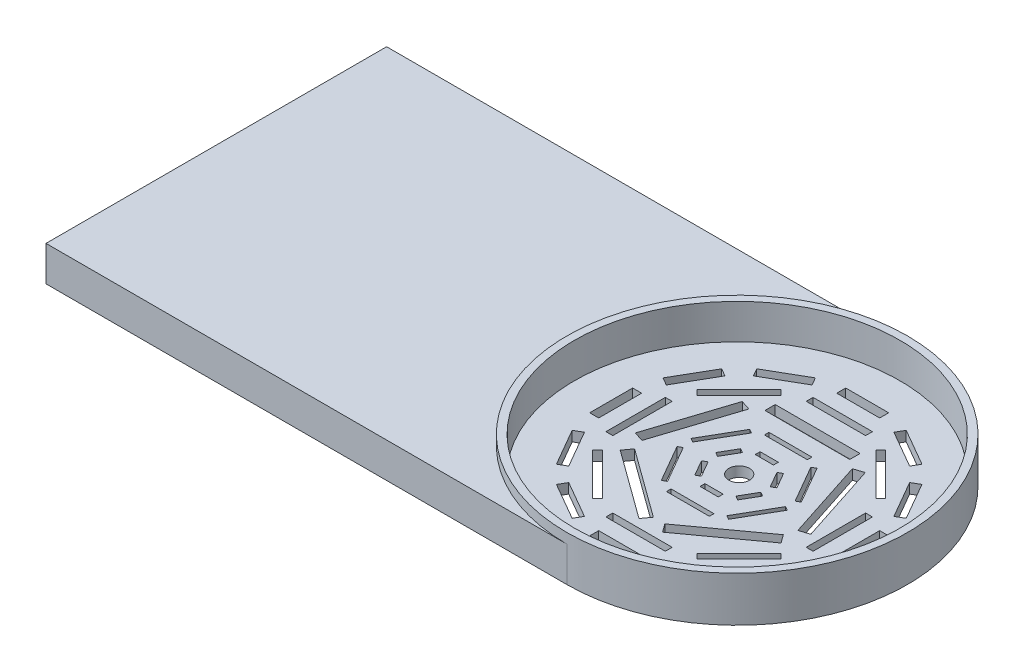
SolidWorks part; units mm, degrees
ref_plane "前视基准面" through (0, 0, 0) normal (0, 0, 1) x (1, 0, 0)
ref_plane "上视基准面" through (0, 0, 0) normal (0, 1, 0) x (1, 0, 0)
ref_plane "右视基准面" through (0, 0, 0) normal (1, 0, 0) x (0, 0, -1)
sketch "草图1" plane through (0, 0, 0) normal (0, 1, 0) x (1, 0, 0)
sketch "草图2" plane through (0, 0, 0) normal (0, 1, 0) x (1, 0, 0)
  circle A1 centre (0, 0) radius 32.5
extrude "凸台-拉伸2" add sketch "草图2" along normal blind 2
sketch "草图3" plane through (0, 2, 0) normal (0, 1, 0) x (1, 0, 0)
  line L0 (4.4198, 4.8381) -> (3.5774, 4.3517)
  line L1 (-1.6852, 6.2644) -> (1.9493, 6.2644)
  line L2 (-1.6852, 6.2644) -> (-1.6852, 5.2916)
  line L3 (-1.6852, 5.2916) -> (1.9493, 5.2916)
  line L4 (1.9493, 6.2644) -> (1.9493, 5.2916)
  line L5 (-1.6852, 6.2644) -> (1.9493, 5.2916) construction
  line L6 (-1.6852, 5.2916) -> (1.9493, 6.2644) construction
  line L7 (4.4198, 4.8381) -> (6.237, 1.6905)
  line L8 (6.237, 1.6905) -> (5.3946, 1.2041)
  line L9 (3.5774, 4.3517) -> (5.3946, 1.2041)
  line L10 (6.237, -1.1622) -> (5.3946, -0.6758)
  line L11 (6.237, -1.1622) -> (4.4198, -4.3097)
  line L12 (4.4198, -4.3097) -> (3.5774, -3.8234)
  line L13 (5.3946, -0.6758) -> (3.5774, -3.8234)
  line L14 (1.9493, -5.736) -> (1.9493, -4.7633)
  line L15 (1.9493, -5.736) -> (-1.6852, -5.736)
  line L16 (-1.6852, -5.736) -> (-1.6852, -4.7633)
  line L17 (1.9493, -4.7633) -> (-1.6852, -4.7633)
  line L18 (-4.1556, -4.3097) -> (-3.3132, -3.8234)
  line L19 (-4.1556, -4.3097) -> (-5.9729, -1.1622)
  line L20 (-5.9729, -1.1622) -> (-5.1305, -0.6758)
  line L21 (-3.3132, -3.8234) -> (-5.1305, -0.6758)
  line L22 (-5.9729, 1.6905) -> (-5.1305, 1.2041)
  line L23 (-5.9729, 1.6905) -> (-4.1556, 4.8381)
  line L24 (-4.1556, 4.8381) -> (-3.3132, 4.3517)
  line L25 (-5.1305, 1.2041) -> (-3.3132, 4.3517)
  line L26 (6.8534, 9.0957) -> (10.35, 1.2124) construction
  line L27 (-4.1556, 10.5008) -> (4.4198, 10.5008)
  line L28 (-4.1556, 10.5008) -> (-4.1556, 9.5872)
  line L29 (-4.1556, 9.5872) -> (4.4198, 9.5872)
  line L30 (4.4198, 10.5008) -> (4.4198, 9.5872)
  line L31 (-4.1556, 10.5008) -> (4.4198, 9.5872) construction
  line L32 (-4.1556, 9.5872) -> (4.4198, 10.5008) construction
  line L33 (6.0623, 8.639) -> (11.1411, 1.6692) construction
  line L34 (6.8534, 9.0957) -> (6.0623, 8.639)
  line L35 (6.8534, 9.0957) -> (11.1411, 1.6692)
  line L36 (11.1411, 1.6692) -> (10.35, 1.2124)
  line L37 (6.0623, 8.639) -> (10.35, 1.2124)
  line L38 (11.1411, -1.1409) -> (6.0623, -8.1106) construction
  line L39 (10.35, -0.6841) -> (6.8534, -8.5674) construction
  line L40 (11.1411, -1.1409) -> (10.35, -0.6841)
  line L41 (11.1411, -1.1409) -> (6.8534, -8.5674)
  line L42 (6.8534, -8.5674) -> (6.0623, -8.1106)
  line L43 (10.35, -0.6841) -> (6.0623, -8.1106)
  line L44 (4.4198, -9.9725) -> (-4.1556, -9.0589) construction
  line L45 (4.4198, -9.0589) -> (-4.1556, -9.9725) construction
  line L46 (4.4198, -9.9725) -> (4.4198, -9.0589)
  line L47 (4.4198, -9.9725) -> (-4.1556, -9.9725)
  line L48 (-4.1556, -9.9725) -> (-4.1556, -9.0589)
  line L49 (4.4198, -9.0589) -> (-4.1556, -9.0589)
  line L50 (-6.5893, -8.5674) -> (-10.0858, -0.6841) construction
  line L51 (-5.7981, -8.1106) -> (-10.877, -1.1409) construction
  line L52 (-6.5893, -8.5674) -> (-5.7981, -8.1106)
  line L53 (-6.5893, -8.5674) -> (-10.877, -1.1409)
  line L54 (-10.877, -1.1409) -> (-10.0858, -0.6841)
  line L55 (-5.7981, -8.1106) -> (-10.0858, -0.6841)
  line L56 (-10.877, 1.6692) -> (-5.7981, 8.639) construction
  line L57 (-10.0858, 1.2124) -> (-6.5893, 9.0957) construction
  line L58 (-10.877, 1.6692) -> (-10.0858, 1.2124)
  line L59 (-10.877, 1.6692) -> (-6.5893, 9.0957)
  line L60 (-6.5893, 9.0957) -> (-5.7981, 8.639)
  line L61 (-10.0858, 1.2124) -> (-5.7981, 8.639)
  line L62 (12.4151, 13.1606) -> (15.6938, -3.585) construction
  line L63 (-8.3375, 15.9312) -> (8.6017, 15.9312)
  line L64 (-8.3375, 15.9312) -> (-8.3375, 13.8748)
  line L65 (-8.3375, 13.8748) -> (8.6017, 13.8748)
  line L66 (8.6017, 15.9312) -> (8.6017, 13.8748)
  line L67 (-8.3375, 15.9312) -> (8.6017, 13.8748) construction
  line L68 (-8.3375, 13.8748) -> (8.6017, 15.9312) construction
  line L69 (10.4593, 12.5252) -> (17.6496, -2.9495) construction
  line L70 (12.4151, 13.1606) -> (10.4593, 12.5252)
  line L71 (12.4151, 13.1606) -> (17.6496, -2.9495)
  line L72 (17.6496, -2.9495) -> (15.6938, -3.585)
  line L73 (10.4593, 12.5252) -> (15.6938, -3.585)
  line L74 (16.193, -7.4324) -> (1.2802, -15.7254) construction
  line L75 (14.9843, -5.7688) -> (2.4889, -17.389) construction
  line L76 (16.193, -7.4324) -> (14.9843, -5.7688)
  line L77 (16.193, -7.4324) -> (2.4889, -17.389)
  line L78 (2.4889, -17.389) -> (1.2802, -15.7254)
  line L79 (14.9843, -5.7688) -> (1.2802, -15.7254)
  line L80 (-2.2247, -17.389) -> (-14.7201, -5.7688) construction
  line L81 (-1.016, -15.7254) -> (-15.9288, -7.4324) construction
  line L82 (-2.2247, -17.389) -> (-1.016, -15.7254)
  line L83 (-2.2247, -17.389) -> (-15.9288, -7.4324)
  line L84 (-15.9288, -7.4324) -> (-14.7201, -5.7688)
  line L85 (-1.016, -15.7254) -> (-14.7201, -5.7688)
  line L86 (-17.3854, -2.9495) -> (-10.1952, 12.5252) construction
  line L87 (-15.4297, -3.585) -> (-12.1509, 13.1606) construction
  line L88 (-17.3854, -2.9495) -> (-15.4297, -3.585)
  line L89 (-17.3854, -2.9495) -> (-12.1509, 13.1606)
  line L90 (-12.1509, 13.1606) -> (-10.1952, 12.5252)
  line L91 (-15.4297, -3.585) -> (-10.1952, 12.5252)
  line L92 (9.2005, 24.5465) -> (15.7273, 18.7005) construction
  line L93 (-4.1556, 25.8275) -> (4.4198, 25.8275)
  line L94 (-4.1556, 25.8275) -> (-4.1556, 24.0282)
  line L95 (-4.1556, 24.0282) -> (4.4198, 24.0282)
  line L96 (4.4198, 25.8275) -> (4.4198, 24.0282)
  line L97 (-4.1556, 25.8275) -> (4.4198, 24.0282) construction
  line L98 (-4.1556, 24.0282) -> (4.4198, 25.8275) construction
  line L99 (8.3008, 22.9882) -> (16.627, 20.2588) construction
  line L100 (9.2005, 24.5465) -> (8.3008, 22.9882)
  line L101 (9.2005, 24.5465) -> (16.627, 20.2588)
  line L102 (16.627, 20.2588) -> (15.7273, 18.7005)
  line L103 (8.3008, 22.9882) -> (15.7273, 18.7005)
  line L104 (20.1267, 16.7591) -> (22.8562, 8.4329) construction
  line L105 (18.5685, 15.8594) -> (24.4144, 9.3326) construction
  line L106 (20.1267, 16.7591) -> (18.5685, 15.8594)
  line L107 (20.1267, 16.7591) -> (24.4144, 9.3326)
  line L108 (24.4144, 9.3326) -> (22.8562, 8.4329)
  line L109 (18.5685, 15.8594) -> (22.8562, 8.4329)
  line L110 (25.6954, 4.5519) -> (23.8961, -4.0235) construction
  line L111 (23.8961, 4.5519) -> (25.6954, -4.0235) construction
  line L112 (25.6954, 4.5519) -> (23.8961, 4.5519)
  line L113 (25.6954, 4.5519) -> (25.6954, -4.0235)
  line L114 (25.6954, -4.0235) -> (23.8961, -4.0235)
  line L115 (23.8961, 4.5519) -> (23.8961, -4.0235)
  line L116 (24.4144, -8.8042) -> (18.5685, -15.3311) construction
  line L117 (22.8562, -7.9046) -> (20.1267, -16.2308) construction
  line L118 (24.4144, -8.8042) -> (22.8562, -7.9046)
  line L119 (24.4144, -8.8042) -> (20.1267, -16.2308)
  line L120 (20.1267, -16.2308) -> (18.5685, -15.3311)
  line L121 (22.8562, -7.9046) -> (18.5685, -15.3311)
  line L122 (16.627, -19.7305) -> (8.3008, -22.4599) construction
  line L123 (15.7273, -18.1722) -> (9.2005, -24.0182) construction
  line L124 (16.627, -19.7305) -> (15.7273, -18.1722)
  line L125 (16.627, -19.7305) -> (9.2005, -24.0182)
  line L126 (9.2005, -24.0182) -> (8.3008, -22.4599)
  line L127 (15.7273, -18.1722) -> (8.3008, -22.4599)
  line L128 (4.4198, -25.2992) -> (-4.1556, -23.4998) construction
  line L129 (4.4198, -23.4998) -> (-4.1556, -25.2992) construction
  line L130 (4.4198, -25.2992) -> (4.4198, -23.4998)
  line L131 (4.4198, -25.2992) -> (-4.1556, -25.2992)
  line L132 (-4.1556, -25.2992) -> (-4.1556, -23.4998)
  line L133 (4.4198, -23.4998) -> (-4.1556, -23.4998)
  line L134 (-8.9363, -24.0182) -> (-15.4632, -18.1722) construction
  line L135 (-8.0367, -22.4599) -> (-16.3628, -19.7305) construction
  line L136 (-8.9363, -24.0182) -> (-8.0367, -22.4599)
  line L137 (-8.9363, -24.0182) -> (-16.3628, -19.7305)
  line L138 (-16.3628, -19.7305) -> (-15.4632, -18.1722)
  line L139 (-8.0367, -22.4599) -> (-15.4632, -18.1722)
  line L140 (-19.8626, -16.2308) -> (-22.592, -7.9046) construction
  line L141 (-18.3043, -15.3311) -> (-24.1503, -8.8042) construction
  line L142 (-19.8626, -16.2308) -> (-18.3043, -15.3311)
  line L143 (-19.8626, -16.2308) -> (-24.1503, -8.8042)
  line L144 (-24.1503, -8.8042) -> (-22.592, -7.9046)
  line L145 (-18.3043, -15.3311) -> (-22.592, -7.9046)
  line L146 (-25.4312, -4.0235) -> (-23.6319, 4.5519) construction
  line L147 (-23.6319, -4.0235) -> (-25.4312, 4.5519) construction
  line L148 (-25.4312, -4.0235) -> (-23.6319, -4.0235)
  line L149 (-25.4312, -4.0235) -> (-25.4312, 4.5519)
  line L150 (-25.4312, 4.5519) -> (-23.6319, 4.5519)
  line L151 (-23.6319, -4.0235) -> (-23.6319, 4.5519)
  line L152 (-24.1503, 9.3326) -> (-18.3043, 15.8594) construction
  line L153 (-22.592, 8.4329) -> (-19.8626, 16.7591) construction
  line L154 (-24.1503, 9.3326) -> (-22.592, 8.4329)
  line L155 (-24.1503, 9.3326) -> (-19.8626, 16.7591)
  line L156 (-19.8626, 16.7591) -> (-18.3043, 15.8594)
  line L157 (-22.592, 8.4329) -> (-18.3043, 15.8594)
  line L158 (-16.3628, 20.2588) -> (-8.0367, 22.9882) construction
  line L159 (-15.4632, 18.7005) -> (-8.9363, 24.5465) construction
  line L160 (-16.3628, 20.2588) -> (-15.4632, 18.7005)
  line L161 (-16.3628, 20.2588) -> (-8.9363, 24.5465)
  line L162 (-8.9363, 24.5465) -> (-8.0367, 22.9882)
  line L163 (-15.4632, 18.7005) -> (-8.0367, 22.9882)
  line L164 (9.5928, 18.1115) -> (10.5615, 19.0801)
  line L165 (-5.7981, 19.5739) -> (6.0623, 19.5739)
  line L166 (-5.7981, 19.5739) -> (-5.7981, 20.9437)
  line L167 (-5.7981, 20.9437) -> (6.0623, 20.9437)
  line L168 (6.0623, 19.5739) -> (6.0623, 20.9437)
  line L169 (-5.7981, 19.5739) -> (6.0623, 20.9437) construction
  line L170 (-5.7981, 20.9437) -> (6.0623, 19.5739) construction
  line L171 (9.5928, 18.1115) -> (17.9794, 9.7249)
  line L172 (17.9794, 9.7249) -> (18.948, 10.6935)
  line L173 (10.5615, 19.0801) -> (18.948, 10.6935)
  line L174 (19.4418, 6.1943) -> (20.8116, 6.1943)
  line L175 (19.4418, 6.1943) -> (19.4418, -5.666)
  line L176 (19.4418, -5.666) -> (20.8116, -5.666)
  line L177 (20.8116, 6.1943) -> (20.8116, -5.666)
  line L178 (17.9794, -9.1966) -> (18.948, -10.1652)
  line L179 (17.9794, -9.1966) -> (9.5928, -17.5831)
  line L180 (9.5928, -17.5831) -> (10.5615, -18.5518)
  line L181 (18.948, -10.1652) -> (10.5615, -18.5518)
  line L182 (6.0623, -19.0456) -> (6.0623, -20.4154)
  line L183 (6.0623, -19.0456) -> (-5.7981, -19.0456)
  line L184 (-5.7981, -19.0456) -> (-5.7981, -20.4154)
  line L185 (6.0623, -20.4154) -> (-5.7981, -20.4154)
  line L186 (-9.3287, -17.5831) -> (-10.2973, -18.5518)
  line L187 (-9.3287, -17.5831) -> (-17.7152, -9.1966)
  line L188 (-17.7152, -9.1966) -> (-18.6838, -10.1652)
  line L189 (-10.2973, -18.5518) -> (-18.6838, -10.1652)
  line L190 (-19.1776, -5.666) -> (-20.5475, -5.666)
  line L191 (-19.1776, -5.666) -> (-19.1776, 6.1943)
  line L192 (-19.1776, 6.1943) -> (-20.5475, 6.1943)
  line L193 (-20.5475, -5.666) -> (-20.5475, 6.1943)
  line L194 (-17.7152, 9.7249) -> (-18.6838, 10.6935)
  line L195 (-17.7152, 9.7249) -> (-9.3287, 18.1115)
  line L196 (-9.3287, 18.1115) -> (-10.2973, 19.0801)
  line L197 (-18.6838, 10.6935) -> (-10.2973, 19.0801)
  circle A0 centre (0.1321, 0.2642) radius 2.0653
  point P2 (0.1321, 5.778)
  point P8 (0.1321, 10.044)
  point P29 (0.1321, 0.2642)
  point P33 (0.1321, 14.903)
  point P35 (8.6017, 5.1541)
  point P40 (8.6017, -4.6258)
  point P45 (0.1321, -9.5157)
  point P50 (-8.3375, -4.6258)
  point P55 (-8.3375, 5.1541)
  point P60 (0.1321, 0.2642)
  point P64 (0.1321, 24.9278)
  point P66 (14.0544, 4.7878)
  point P71 (8.7366, -11.5789)
  point P76 (-8.4724, -11.5789)
  point P81 (-13.7903, 4.7878)
  point P86 (0.1321, 0.2642)
  point P90 (0.1321, 20.2588)
  point P92 (12.4639, 21.6235)
  point P97 (21.4914, 12.596)
  point P102 (24.7957, 0.2642)
  point P107 (21.4914, -12.0677)
  point P112 (12.4639, -21.0952)
  point P117 (0.1321, -24.3995)
  point P122 (-12.1997, -21.0952)
  point P127 (-21.2273, -12.0677)
  point P132 (-24.5316, 0.2642)
  point P137 (-21.2273, 12.596)
  point P142 (-12.1997, 21.6235)
  point P147 (0.1321, 0.2642)
  point P179 (0.1321, 0.2642)
extrude "切除-拉伸1" cut sketch "草图3" against normal blind 2
sketch "草图4" plane through (0, 2, 0) normal (0, 1, 0) x (1, 0, 0)
  circle A0 centre (0, 0) radius 32.5
  circle A1 centre (0, 0) radius 34.005
extrude "凸台-拉伸3" add sketch "草图4" along normal blind 7 and the other way blind 2
sketch "草图5" plane through (0, 0, 0) normal (0, 1, 0) x (1, 0, 0)
  line L1 (-34.005, 34.005) -> (-104.005, 34.005)
  line L2 (-104.005, 34.005) -> (-104.005, -34.005)
  line L3 (-104.005, -34.005) -> (0, -34.005)
  line L4 (-34.005, 34.005) -> (0, 34.005)
  circle A0 centre (0, 0) radius 34.005 construction
  arc A1 (0, 34.005) -> (0, -34.005) centre (0, 0) ccw
  point P5 (-34.005, 34.005)
extrude "凸台-拉伸4" add sketch "草图5" along normal blind 7
